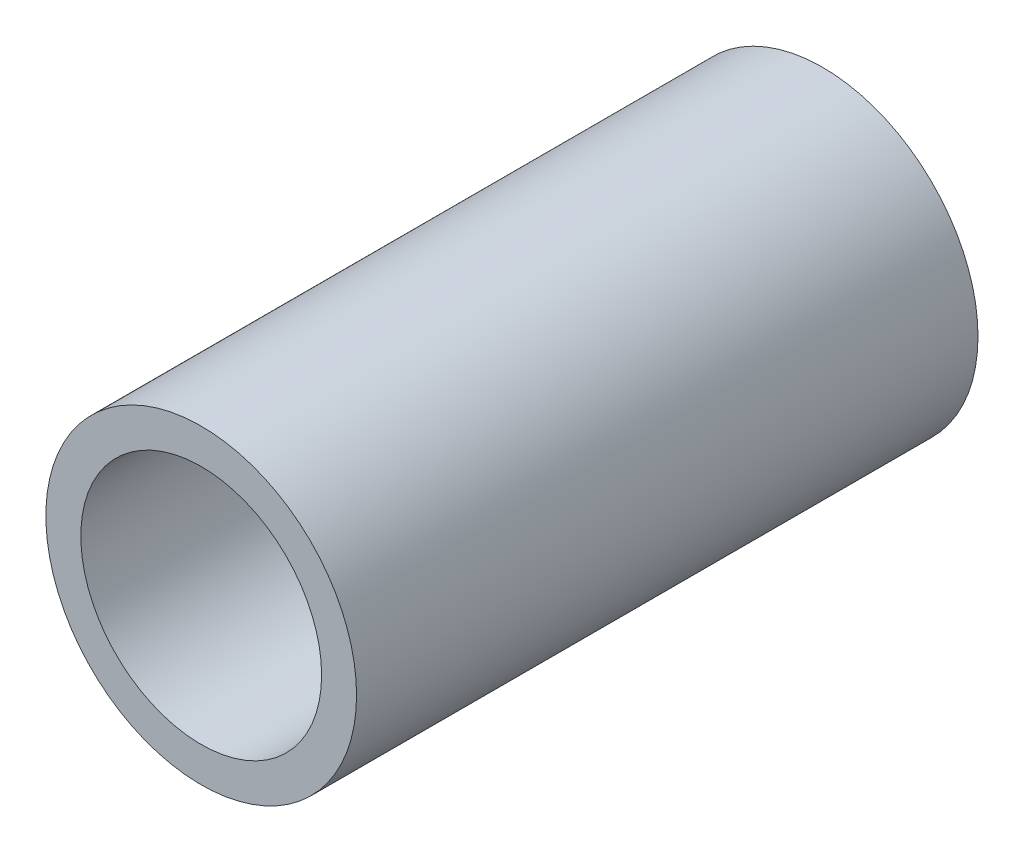
SolidWorks part; units mm, degrees
ref_plane "Спереди" through (0, 0, 0) normal (0, 0, 1) x (1, 0, 0)
ref_plane "Сверху" through (0, 0, 0) normal (0, 1, 0) x (1, 0, 0)
ref_plane "Справа" through (0, 0, 0) normal (1, 0, 0) x (0, 0, -1)
sketch "Эскиз1" plane through (0, 0, 0) normal (0, 0, 1) x (1, 0, 0)
  circle A0 centre (0, 0) radius 1
  circle A1 centre (0, 0) radius 0.775
extrude "Бобышка-Вытянуть1" add sketch "Эскиз1" along normal blind 4
